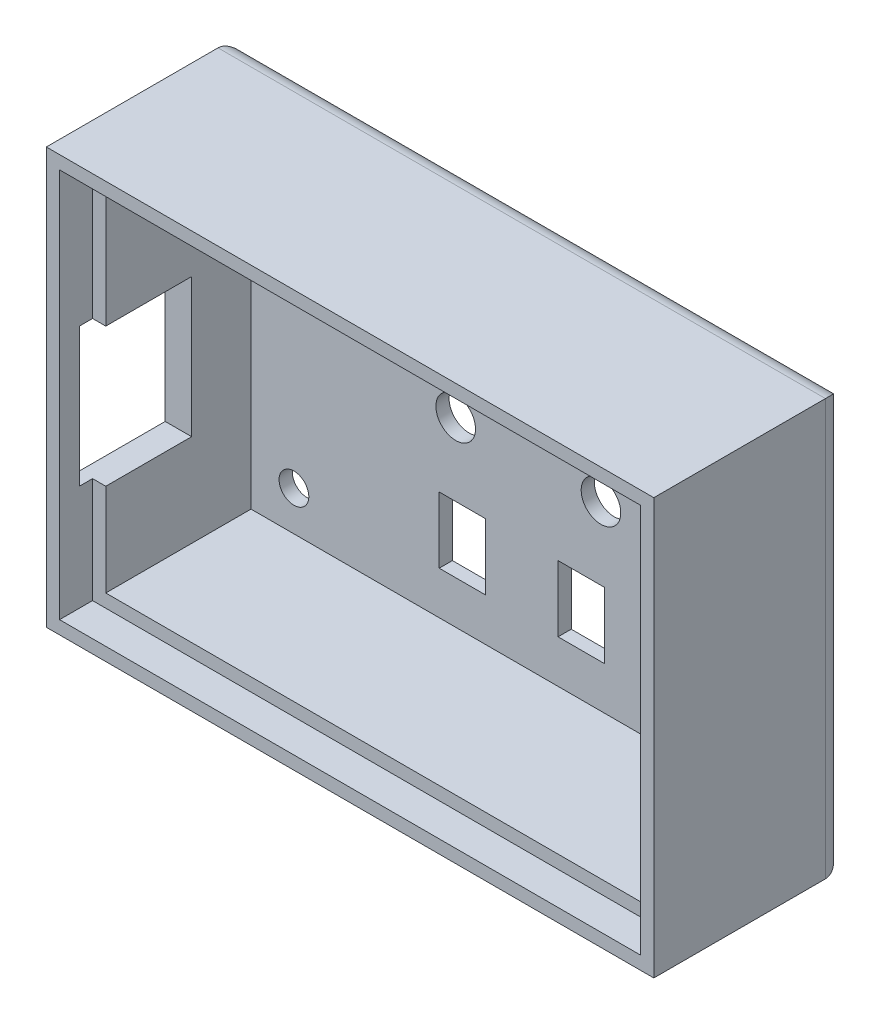
SolidWorks part; units mm, degrees
ref_plane "Front Plane" through (0, 0, 0) normal (0, 0, 1) x (1, 0, 0)
ref_plane "Top Plane" through (0, 0, 0) normal (0, 1, 0) x (1, 0, 0)
ref_plane "Right Plane" through (0, 0, 0) normal (1, 0, 0) x (0, 0, -1)
sketch "Sketch3" plane through (0, 0, 0) normal (0, 0, 1) x (1, 0, 0)
  line L1 (0, 0) -> (92, 0)
  line L2 (0, 0) -> (0, 63)
  line L3 (0, 63) -> (92, 63)
  line L4 (92, 0) -> (92, 63)
  line L5 (8, 55.5) -> (84.5, 55.5)
  line L6 (8, 55.5) -> (8, 7.5)
  line L7 (8, 7.5) -> (84.5, 7.5)
  line L8 (84.5, 55.5) -> (84.5, 7.5)
  line L29 (75, 20.5) -> (68, 20.5)
  line L30 (75, 20.5) -> (75, 10.5)
  line L31 (75, 10.5) -> (68, 10.5)
  line L32 (68, 20.5) -> (68, 10.5)
  line L33 (57.5, 20.5) -> (50.5, 20.5)
  line L34 (57.5, 20.5) -> (57.5, 10.5)
  line L35 (57.5, 10.5) -> (50.5, 10.5)
  line L36 (50.5, 20.5) -> (50.5, 10.5)
  line L37 (39.5, 20.5) -> (32.5, 20.5)
  line L38 (39.5, 20.5) -> (39.5, 10.5)
  line L39 (39.5, 10.5) -> (32.5, 10.5)
  line L40 (32.5, 20.5) -> (32.5, 10.5)
  circle A1 centre (35, 31.5) radius 3
  circle A2 centre (57, 31.5) radius 3
  circle A3 centre (77, 31.5) radius 3
  circle A4 centre (82, 53) radius 2.25
  circle A5 centre (82, 10) radius 2.25
  circle A6 centre (10.5, 10) radius 2.25
  circle A7 centre (10.5, 53) radius 2.25
  point P40 (50.5, 15.5)
  dimension "D12" = 6
  dimension "D13" = 6
  dimension "D14" = 6
  dimension "D23" = 4.5
  dimension "D24" = 4.5
  dimension "D25" = 4.5
  dimension "D26" = 4.5
  dimension "D1" = 63
  dimension "D2" = 92
  dimension "D3" = 48
  dimension "D4" = 76.5
  dimension "D5" = 7.5
  dimension "D6" = 8
  dimension "D7" = 7.5
  dimension "D8" = 7.5
  dimension "D9" = 22
  dimension "D10" = 20
  dimension "D15" = 24
  dimension "D16" = 24
  dimension "D17" = 24
  dimension "D19" = 9.5
  dimension "D20" = 7
  dimension "D22" = 10
  dimension "D27" = 2.5
  dimension "D28" = 2.5
  dimension "D29" = 2.5
  dimension "D30" = 2.5
  dimension "D31" = 2.5
  dimension "D32" = 2.5
  dimension "D33" = 2.5
  dimension "D34" = 2.5
  dimension "D35" = 10.5
  dimension "D36" = 7
  dimension "D37" = 5
  dimension "D38" = 3
  dimension "D39" = 3
  dimension "D40" = 11
  dimension "D41" = 7
  dimension "D42" = 3
  dimension "D43" = 10
extrude "Boss-Extrude3" add sketch "Sketch3" along normal blind 29
sketch "Sketch4" plane through (0, 0, 29) normal (0, 0, 1) x (1, 0, 0)
  line L0 (0, 0) -> (0, 63) construction
  line L1 (4, 59) -> (88, 59)
  line L2 (4, 59) -> (4, 4)
  line L3 (4, 4) -> (88, 4)
  line L4 (88, 59) -> (88, 4)
  line L5 (0, 0) -> (92, 0) construction
  line L6 (0, 63) -> (92, 63) construction
  line L7 (92, 0) -> (92, 63) construction
  dimension "D1" = 4
  dimension "D2" = 4
  dimension "D3" = 4
  dimension "D4" = 4
extrude "Cut-Extrude1" cut sketch "Sketch4" against normal blind 27
sketch "Sketch5" plane through (0, 0, 29) normal (0, 0, 1) x (1, 0, 0)
  line L0 (0, 0) -> (0, 63) construction
  line L1 (2, 61) -> (90, 61)
  line L2 (2, 61) -> (2, 2)
  line L3 (2, 2) -> (90, 2)
  line L4 (90, 61) -> (90, 2)
  line L5 (0, 63) -> (92, 63) construction
  line L6 (92, 0) -> (92, 63) construction
  line L7 (0, 0) -> (92, 0) construction
  dimension "D1" = 2
  dimension "D2" = 2
  dimension "D3" = 2
  dimension "D4" = 2
extrude "Cut-Extrude2" cut sketch "Sketch5" against normal blind 5
fillet "Fillet1" radius 3 4 edges at (46, 0, 0) (0, 31.5, 0) (46, 63, 0) (92, 31.5, 0)
sketch "Sketch6" plane through (0, 0, 0) normal (-1, 0, 0) x (0, 0, 1)
  line L0 (29, 0) -> (3, 0) construction
  line L1 (26, 18) -> (11, 18)
  line L2 (26, 18) -> (26, 39)
  line L3 (26, 39) -> (11, 39)
  line L4 (11, 18) -> (11, 39)
  line L5 (29, 0) -> (29, 63) construction
  dimension "D1" = 18
  dimension "D2" = 21
  dimension "D3" = 15
  dimension "D4" = 3
extrude "Cut-Extrude3" cut sketch "Sketch6" against normal blind 5
